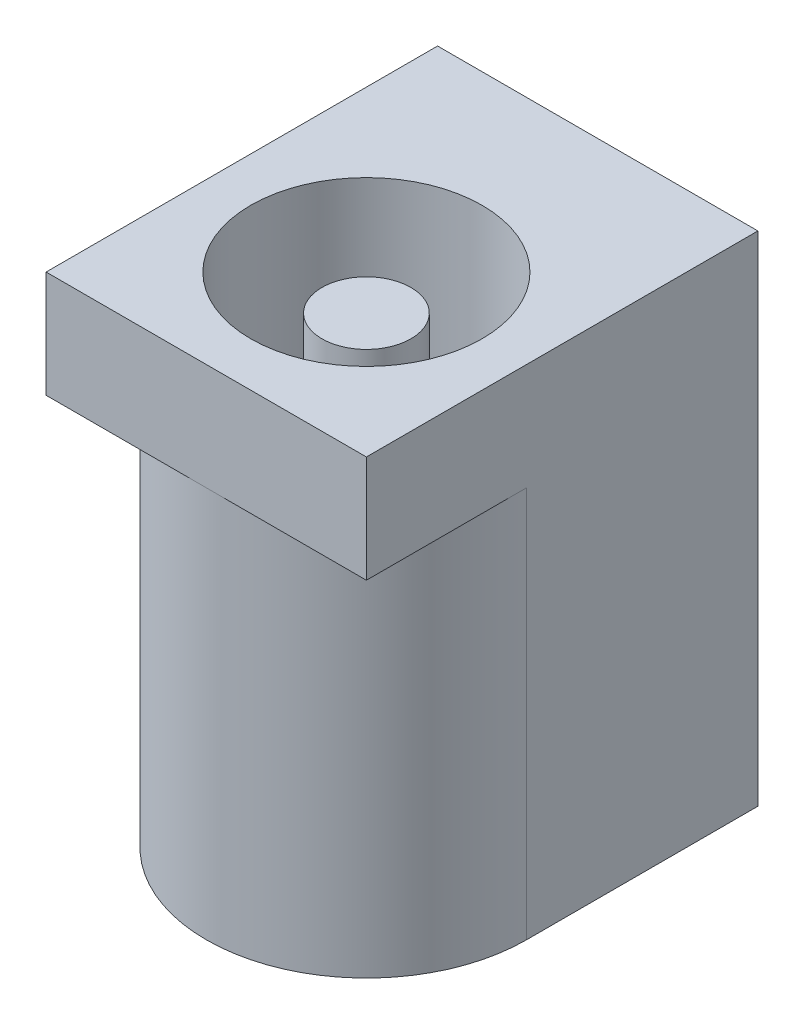
SolidWorks part; units mm, degrees
ref_plane "Front Plane" through (0, 0, 0) normal (0, 0, 1) x (1, 0, 0)
ref_plane "Top Plane" through (0, 0, 0) normal (0, 1, 0) x (1, 0, 0)
ref_plane "Right Plane" through (0, 0, 0) normal (1, 0, 0) x (0, 0, -1)
sketch "Sketch1" plane through (0, 0, 0) normal (0, 0, 1) x (1, 0, 0)
  line L1 (-4.5, 3) -> (4.5, 3)
  line L2 (-4.5, 3) -> (-4.5, 0)
  line L3 (-4.5, 0) -> (4.5, 0)
  line L4 (4.5, 3) -> (4.5, 0)
  dimension "D1" = 9
  dimension "D2" = 3
extrude "Boss-Extrude1" add sketch "Sketch1" along normal blind 11
sketch "Sketch2" plane through (0, 0, 0) normal (0, -1, 0) x (1, 0, 0)
  line L0 (4.5, 11) -> (4.5, 0) construction
  line L1 (-4.5, 0) -> (4.5, 0)
  line L2 (-4.5, 0) -> (-4.5, 6.5)
  line L3 (-4.5, 6.5) -> (4.5, 6.5) construction
  line L4 (4.5, 0) -> (4.5, 6.5)
  line L5 (-4.5, 11) -> (4.5, 11) construction
  arc A0 (-4.5, 6.5) -> (4.5, 6.5) centre (0, 6.5) cw
extrude "Boss-Extrude2" add sketch "Sketch2" along normal blind 11
sketch "Sketch3" plane through (0, 3, 0) normal (0, 1, 0) x (1, 0, 0)
  line L0 (0, 0) -> (0, -6.5) construction
  line L2 (3.25, -6.5) -> (4.5, -6.5) construction
  line L3 (4.5, -11) -> (4.5, 0) construction
  line L4 (0, -9.75) -> (0, -11) construction
  line L5 (4.5, -11) -> (-4.5, -11) construction
  circle A0 centre (0, -6.5) radius 3.25
  dimension "D1" = 6.5
extrude "Cut-Extrude1" cut sketch "Sketch3" against normal blind 13
sketch "Sketch4" plane through (0, -10, 0) normal (0, 1, 0) x (1, 0, 0)
  circle A0 centre (0, -6.5) radius 1.25
  circle A1 centre (0, -6.5) radius 3.25 construction
  dimension "D1" = 2.5
extrude "Boss-Extrude3" add sketch "Sketch4" along normal offset from surface (12 mm away) 1 up to face at (-3.25, 3, 6.5)
